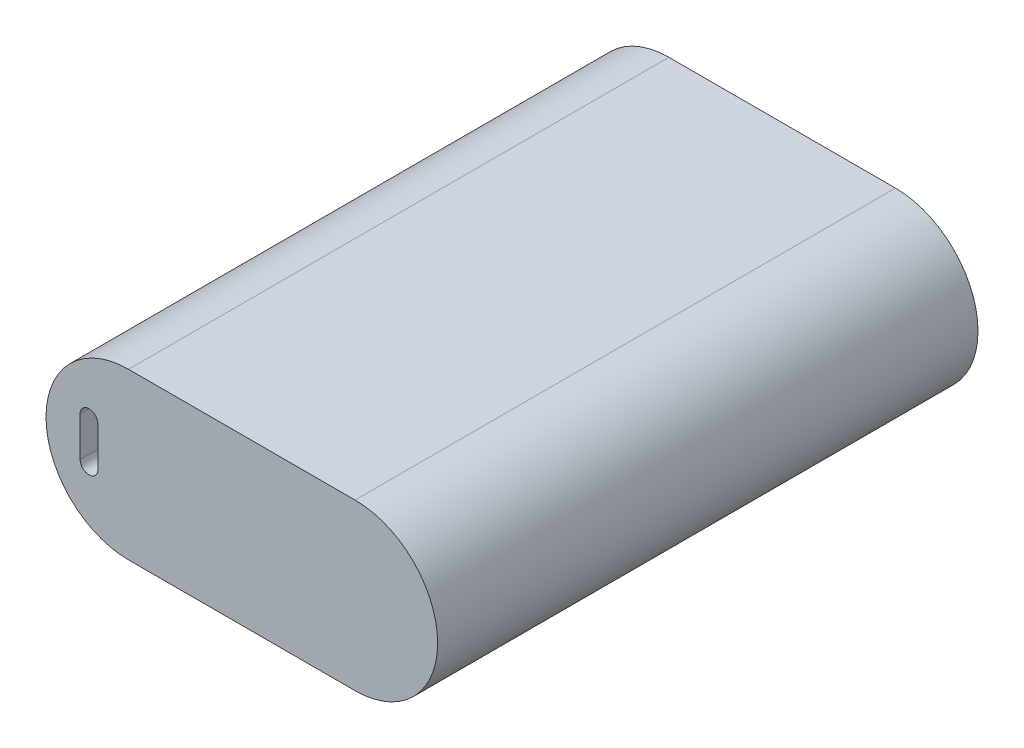
SolidWorks part; units mm, degrees
ref_plane "Přední rovina" through (0, 0, 0) normal (0, 0, 1) x (1, 0, 0)
ref_plane "Vrchní rovina" through (0, 0, 0) normal (0, 1, 0) x (1, 0, 0)
ref_plane "Pravá rovina" through (0, 0, 0) normal (1, 0, 0) x (0, 0, -1)
sketch "Skica1" plane through (0, 0, 0) normal (0, 0, 1) x (1, 0, 0)
  line L0 (0, 0) -> (0, 24.2) construction
  line L1 (0, 12.1) -> (45.3, 12.1) construction
  line L2 (0, 12.1) -> (33.2, 12.1) construction
  line L3 (0, 24.2) -> (33.2, 24.2)
  line L4 (0, 0) -> (33.2, 0)
  arc A0 (0, 24.2) -> (0, 0) centre (0, 12.1) ccw
  arc A1 (33.2, 0) -> (33.2, 24.2) centre (33.2, 12.1) ccw
  point P5 (16.6, 12.1)
  point P11 (-12.1, 12.1)
  point P12 (45.3, 12.1)
  point P13 (0, 24.2)
  point P14 (45.3, 12.1)
  dimension "D1" = 12.1
  dimension "D2" = 24.2
  dimension "D3" = 57.4
extrude "Přidat vysunutím1" add sketch "Skica1" along normal blind 79.2
sketch "Skica2" plane through (0, 0, 0) normal (0, 0, -1) x (-1, 0, 0)
  line L0 (12.1, 12.1) -> (-45.3, 12.1) construction
  line L1 (7.7, 18.6) -> (2.6, 18.6)
  line L2 (7.7, 18.6) -> (7.7, 5.6)
  line L3 (7.7, 5.6) -> (2.6, 5.6)
  line L4 (2.6, 18.6) -> (2.6, 5.6)
  arc A0 (0, 0) -> (0, 24.2) centre (0, 12.1) ccw construction
  arc A1 (-33.2, 24.2) -> (-33.2, 0) centre (-33.2, 12.1) ccw construction
  point P7 (12.1, 12.1)
  dimension "D1" = 13
  dimension "D2" = 5.1
  dimension "D3" = 4.4
  dimension "D4" = 6.5
extrude "Odebrat vysunutím1" cut sketch "Skica2" against normal blind 10
sketch "Skica3" plane through (0, 0, 79.2) normal (0, 0, 1) x (1, 0, 0)
  line L0 (-12.1, 12.1) -> (45.3, 12.1) construction
  line L1 (-5.8, 9.2) -> (-5.8, 15) construction
  line L2 (-7.1, 9.2) -> (-7.1, 15)
  line L3 (-4.5, 9.2) -> (-4.5, 15)
  arc A0 (0, 24.2) -> (0, 0) centre (0, 12.1) ccw construction
  arc A1 (33.2, 0) -> (33.2, 24.2) centre (33.2, 12.1) ccw construction
  arc A2 (-7.1, 9.2) -> (-4.5, 9.2) centre (-5.8, 9.2) ccw
  arc A3 (-4.5, 15) -> (-7.1, 15) centre (-5.8, 15) ccw
  point P10 (-5.8, 12.1)
  point P15 (-5.8, 7.9)
  point P16 (-5.8, 16.3)
  dimension "D1" = 8.4
  dimension "D2" = 2.6
  dimension "D3" = 4.2
  dimension "D4" = 5
extrude "Odebrat vysunutím2" cut sketch "Skica3" against normal blind 6.65
